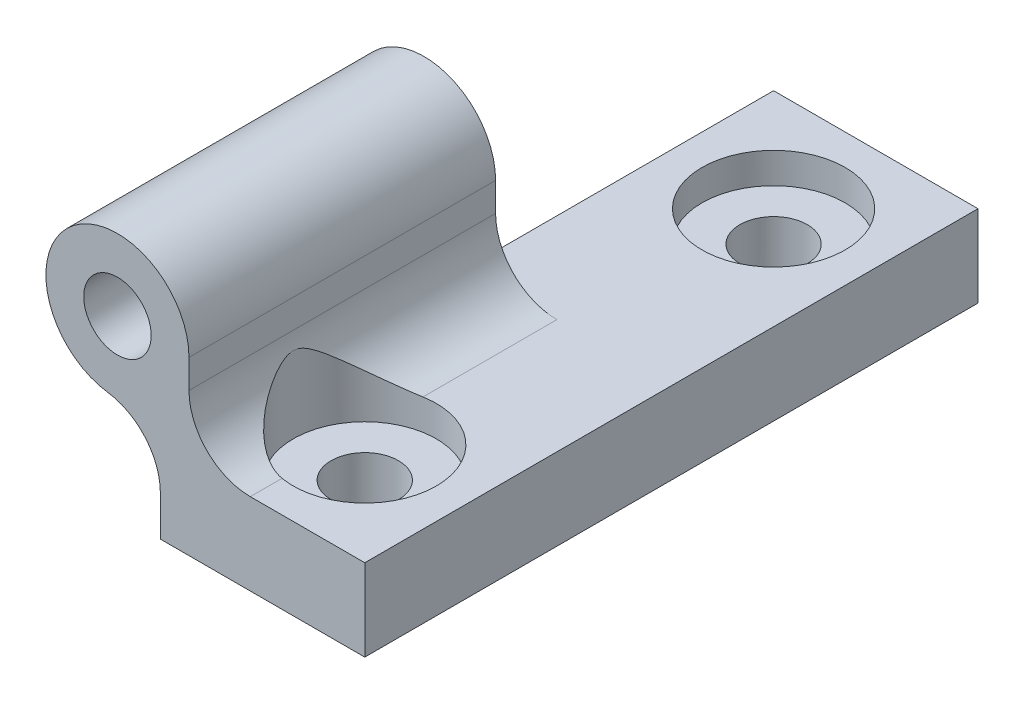
SolidWorks part; units mm, degrees
ref_plane "Front Plane" through (0, 0, 0) normal (0, 0, 1) x (1, 0, 0)
ref_plane "Top Plane" through (0, 0, 0) normal (0, 1, 0) x (1, 0, 0)
ref_plane "Right Plane" through (0, 0, 0) normal (1, 0, 0) x (0, 0, -1)
sketch "Sketch1" plane through (0, 0, 0) normal (0, 0, 1) x (1, 0, 0)
  line L0 (0, 4) -> (0, 5.6)
  line L1 (0, 0) -> (10, 0)
  line L2 (0, 0) -> (0, 4)
  line L3 (0, 4) -> (10, 4)
  line L4 (10, 0) -> (10, 4)
  line L5 (1.4, 8.4) -> (1.4, 4)
  circle A0 centre (-2.1, 8.4) radius 3.5
  circle A1 centre (-2.1, 8.4) radius 1.65
  dimension "D3" = 8.4
  dimension "D4" = 2.1
  dimension "D5" = 7
  dimension "D6" = 3.3
  dimension "D1" = 10
  dimension "D2" = 4
extrude "Boss-Extrude1" add sketch "Sketch1" against normal blind 30 contours A0 A1 | A0 L0 L3 L5 | L1 L4 L3 L2
fillet "Fillet1" radius 3 1 edges at (1.4, 4, -15)
fillet "Fillet2" radius 3 1 edges at (0, 5.6, -15)
sketch "Sketch2" plane through (0, 0, -30) normal (0, 0, -1) x (-1, 0, 0)
  line L1 (-4.4, 4) -> (0, 4)
  line L4 (0, 4) -> (0, 0)
  line L6 (-4.4, 4) -> (-4.4, 12.8785)
  line L7 (-4.4, 12.8785) -> (6.8834, 12.8785)
  line L8 (6.8834, 4) -> (6.8834, 12.8785)
  line L11 (0, 0) -> (6.8834, 0)
  line L12 (6.8834, 4) -> (6.8834, 0)
  arc A0 (-4.4, 4) -> (-1.4, 7) centre (-4.4, 7) ccw construction
extrude "Cut-Extrude1" cut sketch "Sketch2" against normal blind 15
sketch "Sketch3" plane through (0, 4, 0) normal (0, 1, 0) x (1, 0, 0)
  line L0 (4.4, 0) -> (10, 0) construction
  line L1 (10, 30) -> (10, 0) construction
  line L2 (0, 30) -> (10, 30) construction
  circle A0 centre (5, 5) radius 1.65
  circle A1 centre (5, 25) radius 1.65
  dimension "D1" = 5
  dimension "D2" = 5
  dimension "D3" = 5
  dimension "D4" = 5
  dimension "D5" = 3.3
  dimension "D6" = 3.3
extrude "Cut-Extrude2" cut sketch "Sketch3" against normal blind 15 and the other way blind 7
sketch "Sketch4" plane through (0, 4, 0) normal (0, 1, 0) x (1, 0, 0)
  circle A0 centre (5, 5) radius 3.5
  circle A1 centre (5, 25) radius 3.5
  dimension "D1" = 7
  dimension "D2" = 7
extrude "Cut-Extrude3" cut sketch "Sketch4" against normal blind 1.5 and the other way blind 15
